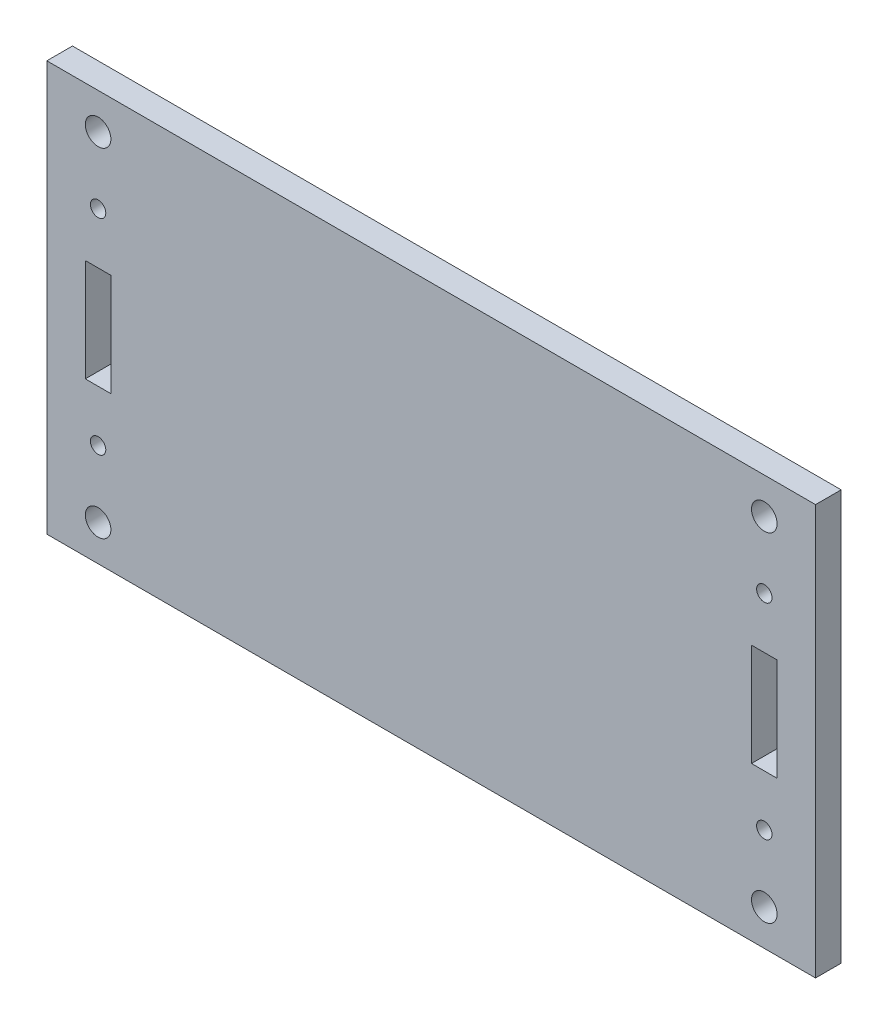
SolidWorks part; units mm, degrees
ref_plane "Front Plane" through (0, 0, 0) normal (0, 0, 1) x (1, 0, 0)
ref_plane "Top Plane" through (0, 0, 0) normal (0, 1, 0) x (1, 0, 0)
ref_plane "Right Plane" through (0, 0, 0) normal (1, 0, 0) x (0, 0, -1)
sketch "Sketch1" plane through (0, 0, 0) normal (0, 0, 1) x (1, 0, 0)
  line L0 (0, 50) -> (0, -30) construction
  line L1 (-75, 50) -> (75, 50)
  line L2 (-75, 50) -> (-75, -30)
  line L3 (-75, -30) -> (75, -30)
  line L4 (75, 50) -> (75, -30)
  line L5 (67.5, 0) -> (62.5, 20) construction
  line L6 (-67.5, 20) -> (-62.5, 20)
  line L7 (-75, 10) -> (75, 10) construction
  line L8 (-67.5, 20) -> (-67.5, 0)
  line L9 (-67.5, 0) -> (-62.5, 0)
  line L10 (-62.5, 20) -> (-62.5, 0)
  line L11 (-67.5, 20) -> (-62.5, 0) construction
  line L12 (-67.5, 0) -> (-62.5, 20) construction
  line L13 (67.5, 20) -> (62.5, 0) construction
  line L14 (62.5, 20) -> (62.5, 0)
  line L15 (67.5, 0) -> (62.5, 0)
  line L16 (67.5, 20) -> (67.5, 0)
  line L17 (67.5, 20) -> (62.5, 20)
  circle A0 centre (-65, 43) radius 2.5
  circle A1 centre (65, 43) radius 2.5
  circle A2 centre (65, -23) radius 2.5
  circle A3 centre (-65, -23) radius 2.5
  circle A4 centre (-65, 30) radius 1.5
  circle A5 centre (-65, -10) radius 1.5
  circle A6 centre (65, -10) radius 1.5
  circle A7 centre (65, 30) radius 1.5
  point P0 (0, 0)
  point P22 (-65, 10)
  point P33 (65, 10)
  dimension "D3" = 10
  dimension "D5" = 20
  dimension "D4" = 7
  dimension "D8" = 10
  dimension "D1" = 150
  dimension "D2" = 80
  dimension "D6" = 10
  dimension "D7" = 5
extrude "Boss-Extrude1" add sketch "Sketch1" along normal blind 5
